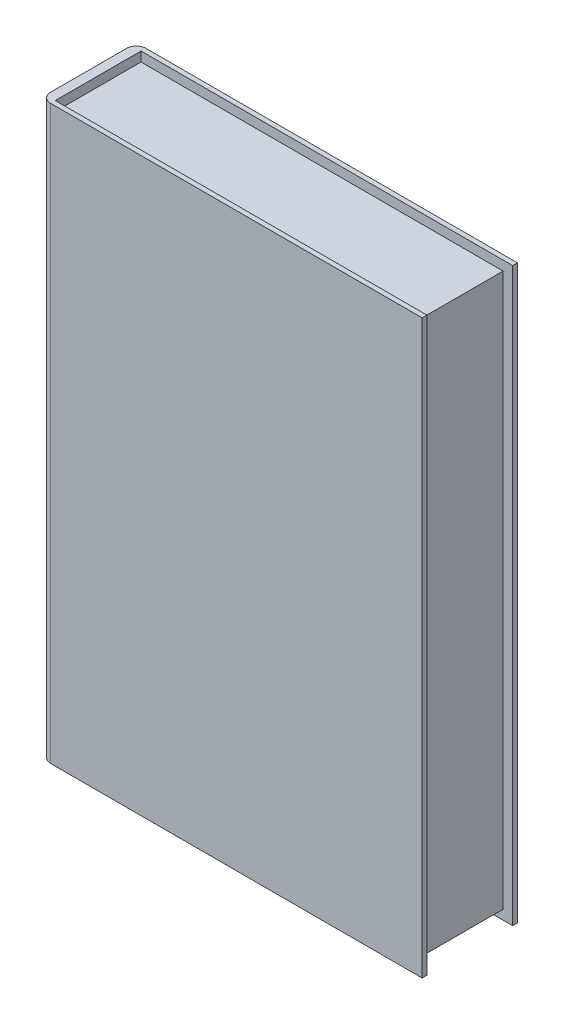
SolidWorks part; units mm, degrees
ref_plane "Front Plane" through (0, 0, 0) normal (0, 0, 1) x (1, 0, 0)
ref_plane "Top Plane" through (0, 0, 0) normal (0, 1, 0) x (1, 0, 0)
ref_plane "Right Plane" through (0, 0, 0) normal (1, 0, 0) x (0, 0, -1)
sketch "Sketch7" plane through (0, 0, 0) normal (0, 0, 1) x (1, 0, 0)
  line L1 (-1.5789, 31.8421) -> (78.4211, 31.8421)
  line L2 (-1.5789, 31.8421) -> (-1.5789, -88.1579)
  line L3 (-1.5789, -88.1579) -> (78.4211, -88.1579)
  line L4 (78.4211, 31.8421) -> (78.4211, -88.1579)
  dimension "D1" = 80
  dimension "D2" = 120
extrude "Boss-Extrude2" add sketch "Sketch7" along normal mid plane 20
sketch "Sketch8" plane through (0, 31.8421, 0) normal (0, 1, 0) x (1, 0, 0)
  line L0 (78.4211, -10) -> (78.4211, 10) construction
  line L1 (0.4211, 9) -> (78.4211, 9)
  line L2 (0.4211, 9) -> (0.4211, -9)
  line L3 (0.4211, -9) -> (78.4211, -9)
  line L4 (78.4211, 9) -> (78.4211, -9)
  line L5 (78.4211, 10) -> (-1.5789, 10) construction
  line L6 (-1.5789, -10) -> (-1.5789, 10) construction
  line L7 (78.4211, -10) -> (-1.5789, -10) construction
  dimension "D1" = 1
  dimension "D2" = 2
  dimension "D3" = 1
extrude "Cut-Extrude1" cut sketch "Sketch8" against normal blind 2
sketch "Sketch9" plane through (78.4211, 0, 0) normal (1, 0, 0) x (0, 0, -1)
  line L0 (10, -88.1579) -> (10, 31.8421) construction
  line L1 (-9, 29.8421) -> (9, 29.8421)
  line L2 (-9, 29.8421) -> (-9, -87.1579)
  line L3 (-9, -87.1579) -> (9, -87.1579)
  line L4 (9, 29.8421) -> (9, -87.1579)
  line L5 (-10, -88.1579) -> (10, -88.1579) construction
  line L6 (-10, -88.1579) -> (-10, 31.8421) construction
  dimension "D1" = 1
  dimension "D2" = 1
  dimension "D3" = 1
extrude "Cut-Extrude2" cut sketch "Sketch9" against normal blind 2
sketch "Sketch10" plane through (0, -88.1579, 0) normal (0, -1, 0) x (1, 0, 0)
  line L0 (78.4211, 10) -> (78.4211, -10) construction
  line L1 (0.4211, 9) -> (78.4211, 9)
  line L2 (0.4211, 9) -> (0.4211, -9)
  line L3 (0.4211, -9) -> (78.4211, -9)
  line L4 (78.4211, 9) -> (78.4211, -9)
  line L5 (-1.5789, 10) -> (78.4211, 10) construction
  line L6 (-1.5789, 10) -> (-1.5789, -10) construction
  line L7 (-1.5789, -10) -> (78.4211, -10) construction
  dimension "D1" = 1
  dimension "D2" = 2
  dimension "D3" = 1
extrude "Cut-Extrude3" cut sketch "Sketch10" against normal blind 2
fillet "Fillet1" radius 2 2 edges at (-1.5789, -28.1579, -10) (-1.5789, -28.1579, 10)
